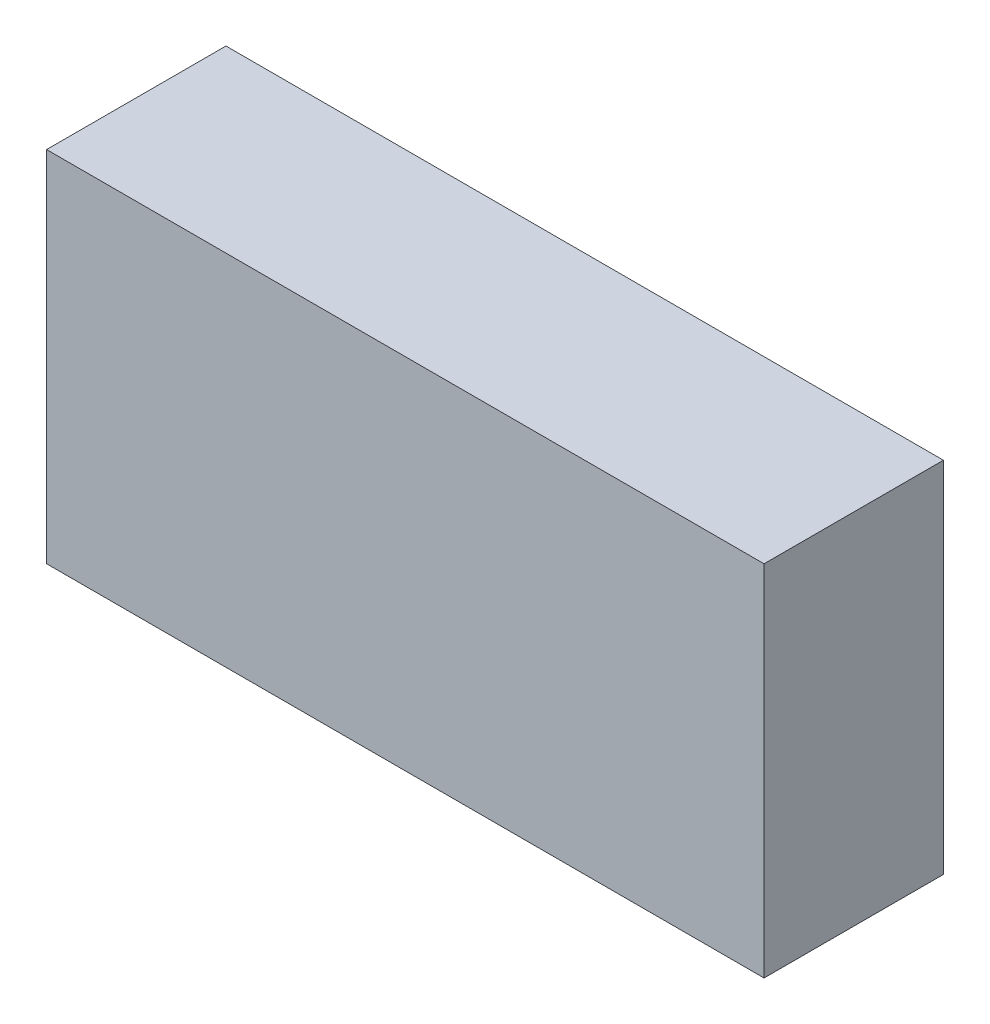
SolidWorks part; units mm, degrees
ref_plane "Front Plane" through (0, 0, 0) normal (0, 0, 1) x (1, 0, 0)
ref_plane "Top Plane" through (0, 0, 0) normal (0, 1, 0) x (1, 0, 0)
ref_plane "Right Plane" through (0, 0, 0) normal (1, 0, 0) x (0, 0, -1)
sketch "Sketch1" plane through (0, 0, 0) normal (0, 0, 1) x (1, 0, 0)
  line L1 (0, 0) -> (80, 0)
  line L2 (0, 0) -> (0, 40)
  line L3 (0, 40) -> (80, 40)
  line L4 (80, 0) -> (80, 40)
  dimension "D1" = 80
  dimension "D2" = 40
extrude "Boss-Extrude1" add sketch "Sketch1" against normal blind 20
ref_plane "Plane1" through (0, 20, 0) normal (0, 1, 0) x (1, 0, 0)
ref_plane "Plane2" through (40, 0, 0) normal (-1, 0, 0) x (0, 0, 1)
sketch "Sketch2" plane through (0, 0, -20) normal (0, 0, -1) x (-1, 0, 0)
  line L0 (0, 11) -> (0, -11) construction
  line L1 (-80, 40) -> (0, 40) construction
  circle A0 centre (-40, 20) radius 10
  dimension "D1" = 20
  dimension "D2" = 40
  dimension "D3" = 20
extrude "Boss-Extrude2" add sketch "Sketch2" along normal blind 5
sketch "Sketch3" plane through (0, 0, -20) normal (0, 0, -1) x (-1, 0, 0)
  line L0 (-80, 40) -> (0, 40) construction
  circle A0 centre (-15, 20) radius 5
  circle A1 centre (-40, 20) radius 10 construction
  point P6 (-15.0358, 19.8996)
  dimension "D1" = 10
  dimension "D2" = 25
  dimension "D3" = 20
extrude "Boss-Extrude3" add sketch "Sketch3" along normal blind 10
mirror "Mirror1" about plane through (40, 0, 0) normal (-1, 0, 0) of "Boss-Extrude3"
